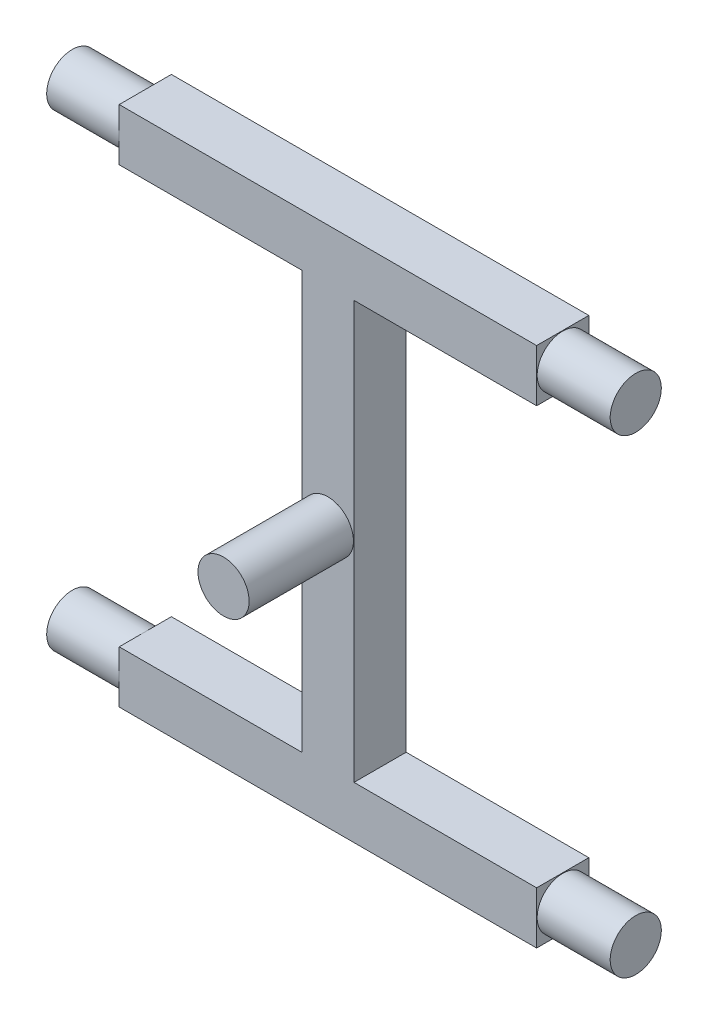
SolidWorks part; units mm, degrees
ref_plane "Front Plane" through (0, 0, 0) normal (0, 0, 1) x (1, 0, 0)
ref_plane "Top Plane" through (0, 0, 0) normal (0, 1, 0) x (1, 0, 0)
ref_plane "Right Plane" through (0, 0, 0) normal (1, 0, 0) x (0, 0, -1)
sketch "Croquis2" plane through (0, 0, 0) normal (0, 0, 1) x (1, 0, 0)
  line L1 (-200, -250) -> (200, -250)
  line L2 (-200, -250) -> (-200, 250)
  line L3 (-200, 250) -> (200, 250)
  line L4 (200, -250) -> (200, 250)
  line L5 (-200, -250) -> (200, 250) construction
  line L6 (-200, 250) -> (200, -250) construction
  point P0 (0, 0)
  dimension "D1" = 500
  dimension "D2" = 400
extrude "Saliente-Extruir3" add sketch "Croquis2" against normal blind 50
sketch "Croquis7" plane through (0, 0, 0) normal (0, 0, 1) x (1, 0, 0)
  line L0 (-200, 200) -> (-25, 200)
  line L1 (-200, 250) -> (-200, -250) construction
  line L2 (-25, 200) -> (-25, -200)
  line L3 (-25, -200) -> (-200, -200)
  line L4 (-200, -200) -> (-200, 200)
  line L5 (-200, -250) -> (200, -250) construction
  line L6 (200, 250) -> (-200, 250) construction
  line L7 (0, 279.5541) -> (0, -329.5661) construction
  line L8 (200, -200) -> (200, 200)
  line L9 (25, -200) -> (200, -200)
  line L10 (25, 200) -> (25, -200)
  line L11 (200, 200) -> (25, 200)
  dimension "D1" = 50
  dimension "D2" = 50
  dimension "D3" = 175
extrude "Cortar-Extruir2" cut sketch "Croquis7" against normal blind 50
sketch "Croquis9" plane through (-200, 0, 0) normal (-1, 0, 0) x (0, 0, 1)
  line L0 (-25, -188.5071) -> (-25, -261.5832) construction
  line L1 (-56.2943, -225) -> (16.2018, -225) construction
  circle A0 centre (-25, -225.0451) radius 24.5
  point P6 (0, 0)
  dimension "D1" = 49
extrude "Saliente-Extruir5" add sketch "Croquis9" along normal blind 70
sketch "Croquis10" plane through (-200, 0, 0) normal (-1, 0, 0) x (0, 0, 1)
  line L0 (-25, 259.8262) -> (-25, 187.6235) construction
  line L1 (18.4524, 223.7248) -> (-68.9358, 223.7248) construction
  circle A0 centre (-25, 223.7248) radius 24.5
  dimension "D1" = 49
extrude "Saliente-Extruir6" add sketch "Croquis10" along normal blind 70
sketch "Croquis12" plane through (0, 0, 0) normal (0, 0, 1) x (1, 0, 0)
  circle A0 centre (0, 0) radius 24.5
  point P2 (0, 0)
  dimension "D1" = 49
sketch "Croquis19" plane through (200, 0, 0) normal (1, 0, 0) x (0, 0, -1)
  line L0 (0, -200) -> (50, -250) construction
  line L1 (50, -200) -> (0, -250) construction
  circle A0 centre (25, -225) radius 24.5
  dimension "D1" = 49
extrude "Saliente-Extruir10" add sketch "Croquis19" along normal blind 70
sketch "Croquis20" plane through (200, 0, 0) normal (1, 0, 0) x (0, 0, -1)
  line L0 (0, 250) -> (50, 200) construction
  line L1 (0, 200) -> (50, 250) construction
  circle A0 centre (25, 225) radius 24.5
  dimension "D1" = 49
extrude "Saliente-Extruir11" add sketch "Croquis20" along normal blind 70
extrude "Saliente-Extruir12" add sketch "Croquis12" along normal blind 100 contours A0
